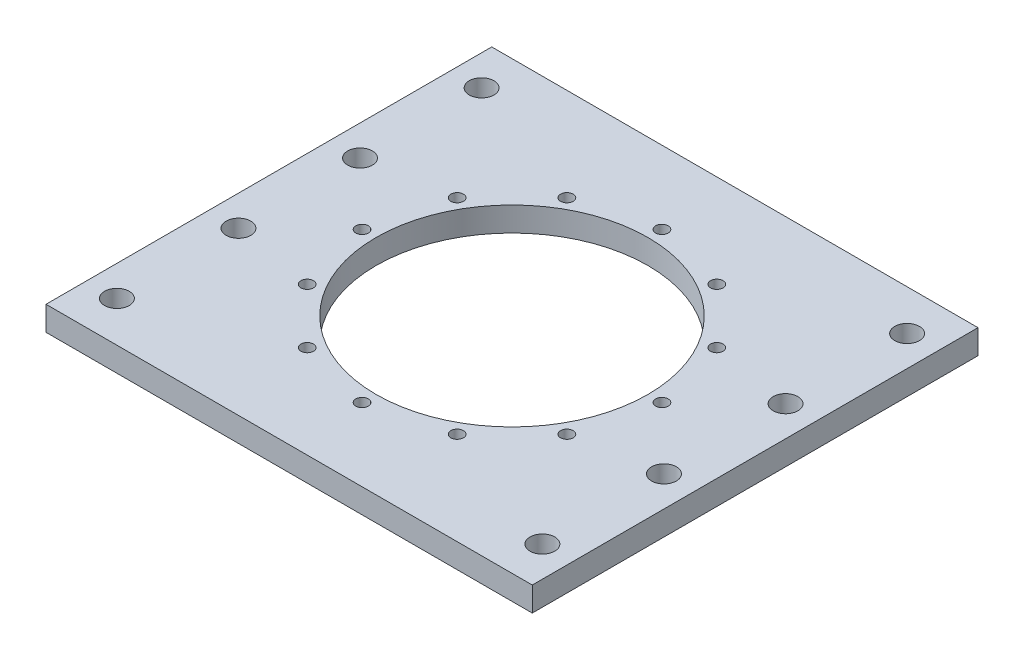
SolidWorks part; units mm, degrees
ref_plane "Front Plane" through (0, 0, 0) normal (0, 0, 1) x (1, 0, 0)
ref_plane "Top Plane" through (0, 0, 0) normal (0, 1, 0) x (1, 0, 0)
ref_plane "Right Plane" through (0, 0, 0) normal (1, 0, 0) x (0, 0, -1)
sketch "Sketch1" plane through (0, 0, 0) normal (0, 1, 0) x (1, 0, 0)
  line L1 (-60, 55) -> (60, 55)
  line L2 (-60, 55) -> (-60, -55)
  line L3 (-60, -55) -> (60, -55)
  line L4 (60, 55) -> (60, -55)
  line L5 (-60, 55) -> (60, -55) construction
  line L6 (-60, -55) -> (60, 55) construction
  point P0 (0, 0)
  dimension "D1" = 120
  dimension "D2" = 110
extrude "Boss-Extrude1" add sketch "Sketch1" along normal blind 6
sketch "Sketch2" plane through (0, 6, 0) normal (0, 1, 0) x (1, 0, 0)
  circle A2 centre (0, 0) radius 33.55
  dimension "D1" = 67.1
extrude "Cut-Extrude1" cut sketch "Sketch2" against normal through all
sketch "Sketch3" plane through (0, 6, 0) normal (0, 1, 0) x (1, 0, 0)
  point P0 (0, 37)
  dimension "D1" = 37
hole_wizard "M3 Clearance Hole1" positions "Sketch3" profile "Sketch4" hole size "M3" standard "ANSI Metric" end condition through all
sketch "Sketch4" plane through (0, 6, -37) normal (1, 0, 0) x (0, 0, 1)
  line L0 (0, 0) -> (0, 6)
  line L1 (0, 6) -> (1.55, 6)
  line L2 (1.55, 6) -> (1.55, 0)
  line L5 (1.55, 0) -> (0, 0)
  line L11 (0, -6.35) -> (0, 107.95) construction
  dimension "Thru Hole Dia." = 3.1
  dimension "Thru Hole Depth" = 6
pattern_circular "CirPattern1" count 12 over 360 about axis through (0, 0, 0) along (0, 1, 0) of "M3 Clearance Hole1"
sketch "Sketch5" plane through (0, 6, 0) normal (0, 1, 0) x (1, 0, 0)
  line L0 (-60, -55) -> (60, -55) construction
  line L1 (60, -55) -> (60, 55) construction
  line L2 (60, 55) -> (-60, 55) construction
  point P0 (52.5, -45)
  point P5 (52.5, -15)
  point P6 (52.5, 15)
  point P7 (52.5, 45)
  dimension "D1" = 10
  dimension "D2" = 7.5
  dimension "D3" = 10
  dimension "D4" = 30
  dimension "D5" = 90
  dimension "D6" = 30
hole_wizard "M6 Clearance Hole2" positions "Sketch5" profile "Sketch6" hole size "M6" standard "ANSI Metric" end condition through all
sketch "Sketch6" plane through (52.5, 6, 45) normal (1, 0, 0) x (0, 0, 1)
  line L0 (0, 0) -> (0, 6)
  line L1 (0, 6) -> (3.05, 6)
  line L2 (3.05, 6) -> (3.05, 0)
  line L5 (3.05, 0) -> (0, 0)
  line L11 (0, -6.35) -> (0, 107.95) construction
  dimension "Thru Hole Dia." = 6.1
  dimension "Thru Hole Depth" = 6
mirror "Mirror1" about plane through (0, 0, 0) normal (1, 0, 0) of "M6 Clearance Hole2"
equation "\"D3@Sketch5\" = \"D1@Sketch5\""
equation "\"D4@Sketch5\" = \"D5@Sketch5\" / 3"
equation "\"D6@Sketch5\" = \"D5@Sketch5\" / 3"
